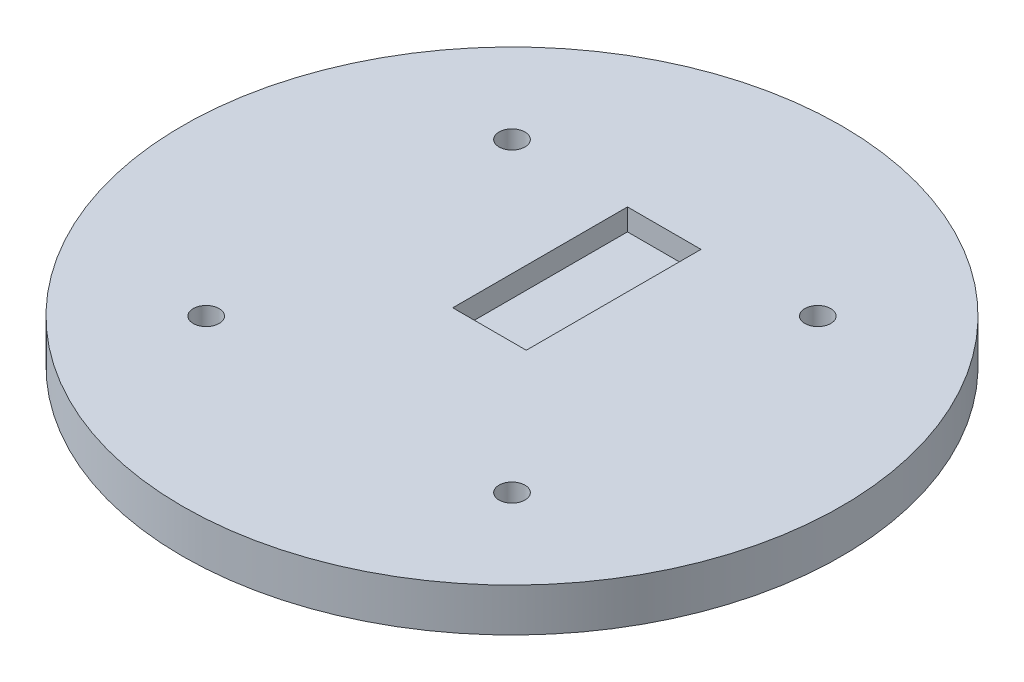
SolidWorks part; units mm, degrees
ref_plane "Front Plane" through (0, 0, 0) normal (0, 0, 1) x (1, 0, 0)
ref_plane "Top Plane" through (0, 0, 0) normal (0, 1, 0) x (1, 0, 0)
ref_plane "Right Plane" through (0, 0, 0) normal (1, 0, 0) x (0, 0, -1)
sketch "Sketch1" plane through (0, 0, 0) normal (0, 1, 0) x (1, 0, 0)
  circle A0 centre (0, 0) radius 38.1
  dimension "D1" = 76.2
extrude "Boss-Extrude1" add sketch "Sketch1" along normal blind 5
sketch "Sketch3" plane through (0, 5, 0) normal (0, 1, 0) x (1, 0, 0)
  line L0 (0, 0) -> (0, 7.5) construction
  line L2 (4.25, 17.6) -> (-4.25, 17.6)
  line L3 (4.25, 17.6) -> (4.25, -2.6)
  line L4 (4.25, -2.6) -> (-4.25, -2.6)
  line L5 (-4.25, 17.6) -> (-4.25, -2.6)
  line L6 (4.25, 17.6) -> (-4.25, -2.6) construction
  line L7 (4.25, -2.6) -> (-4.25, 17.6) construction
  point P7 (0, 7.4826)
  dimension "D1" = 8.5
  dimension "D2" = 20.2
  dimension "D3" = 7.5
extrude "Cut-Extrude2" cut sketch "Sketch3" against normal blind 2.5
sketch "Sketch4" plane through (0, 2.5, 0) normal (0, 1, 0) x (1, 0, 0)
  line L0 (0, 0) -> (0, -1.6) construction
  line L1 (-4.25, -2.6) -> (4.25, -2.6) construction
  line L2 (2.5, -0.6) -> (-2.5, -0.6)
  line L3 (2.5, -0.6) -> (2.5, -2.6)
  line L4 (2.5, -2.6) -> (-2.5, -2.6)
  line L5 (-2.5, -0.6) -> (-2.5, -2.6)
  line L6 (2.5, -0.6) -> (-2.5, -2.6) construction
  line L7 (2.5, -2.6) -> (-2.5, -0.6) construction
  dimension "D1" = 5
  dimension "D2" = 2
extrude "Cut-Extrude4" cut sketch "Sketch4" against normal through all
sketch "Sketch5" plane through (0, 5, 0) normal (0, 1, 0) x (1, 0, 0)
  line L0 (0, 0) -> (25, 0) construction
  line L1 (-17.6777, -17.6777) -> (17.6777, 17.6777) construction
  line L2 (17.6777, -17.6777) -> (-17.6777, 17.6777) construction
  circle A0 centre (0, 0) radius 25 construction
  circle A1 centre (17.6777, 17.6777) radius 1.5
  circle A2 centre (-17.6777, 17.6777) radius 1.5
  circle A3 centre (-17.6777, -17.6777) radius 1.5
  circle A4 centre (17.6777, -17.6777) radius 1.5
  dimension "D1" = 50
  dimension "D6" = 3
  dimension "D7" = 3
  dimension "D8" = 3
  dimension "D9" = 3
  dimension "D2" = 45
  dimension "D3" = 90
  dimension "D4" = 50
  dimension "D5" = 50
extrude "Cut-Extrude5" cut sketch "Sketch5" against normal blind 3
ref_plane "Plane1" through (0, 0, 0) normal (0, 1, 0) x (1, 0, 0)
sketch "Sketch6" plane through (0, 0, 0) normal (0, -1, 0) x (1, 0, 0)
  line L0 (0, 33.1) -> (0, -33.1) construction
  line L1 (33.1, 0) -> (-33.1, 0) construction
  circle A1 centre (0, -33.1) radius 2.5
  circle A2 centre (33.1, 0) radius 2.5
  circle A3 centre (0, 33.1) radius 2.5
  circle A4 centre (-33.1, 0) radius 2.5
  circle A5 centre (0, 0) radius 33.1 construction
  point P12 (0, 0)
  dimension "D1" = 5
  dimension "D2" = 66.2
  dimension "D3" = 33.1
  dimension "D4" = 66.2
  dimension "D5" = 66.2
extrude "Cut-Extrude6" cut sketch "Sketch6" against normal blind 3
